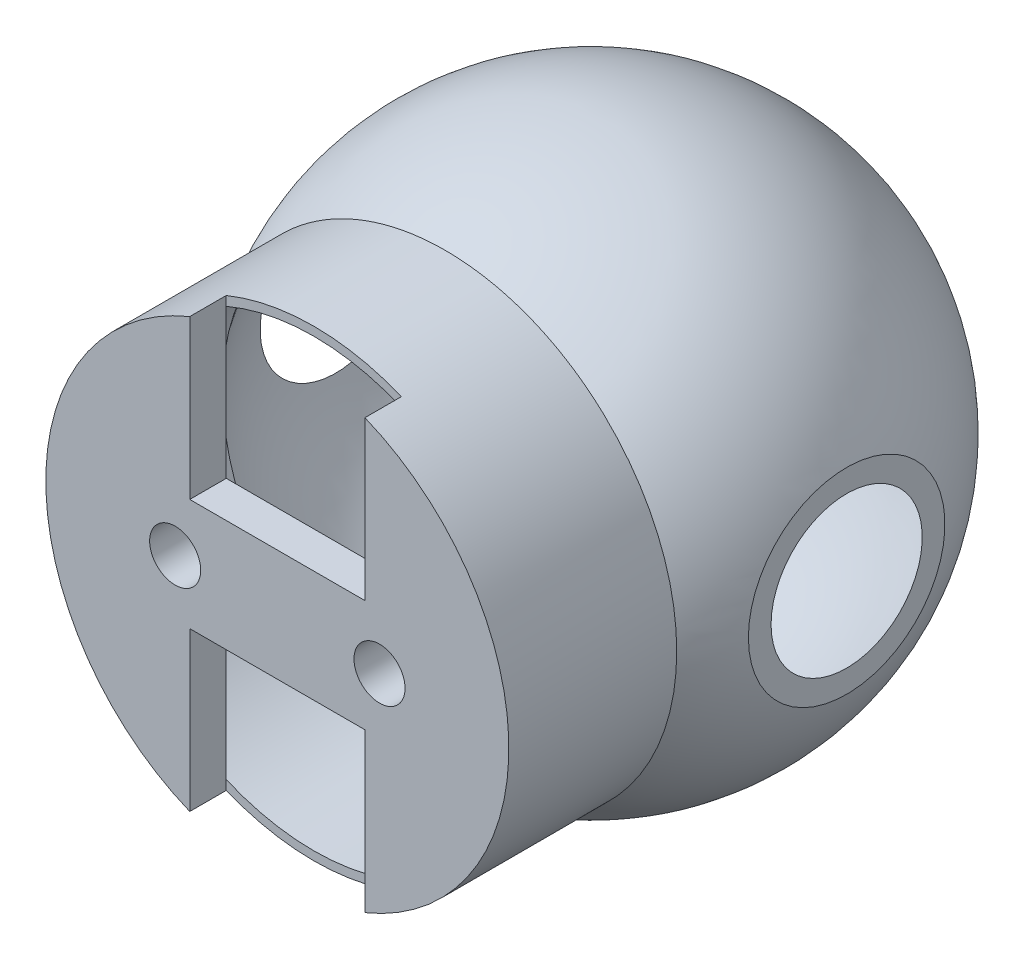
SolidWorks part; units mm, degrees
ref_plane "Front Plane" through (0, 0, 0) normal (0, 0, 1) x (1, 0, 0)
ref_plane "Top Plane" through (0, 0, 0) normal (0, 1, 0) x (1, 0, 0)
ref_plane "Right Plane" through (0, 0, 0) normal (1, 0, 0) x (0, 0, -1)
sketch "Sketch1" plane through (0, 0, 0) normal (0, 0, 1) x (1, 0, 0)
  line L0 (0, 37.5) -> (0, -37.5) construction
  arc A0 (0, -37.5) -> (0, 37.5) centre (0, 0) ccw
  dimension "D1" = 75
revolve "Revolve-Thin4" add sketch "Sketch1" angle 360 about L0 wall 1
ref_plane "Plane1" through (0, 0, 20) normal (0, 0, 1) x (1, 0, 0)
sketch "Sketch2" plane through (0, 0, 20) normal (0, 0, 1) x (1, 0, 0)
  circle A0 centre (0, 0) radius 37.5
  circle A1 centre (0, 0) radius 37.5 construction
extrude "Cut-Extrude1" cut sketch "Sketch2" along normal up to next
ref_plane "Plane3" through (-35, 0, 0) normal (1, 0, 0) x (0, 0, -1)
sketch "Sketch4" plane through (-35, 0, 0) normal (1, 0, 0) x (0, 0, -1)
  circle A0 centre (0, 0) radius 37.5
  arc A1 (-20, -31.7214) -> (-20, 31.7214) centre (0, 0) ccw construction
extrude "Cut-Extrude2" cut sketch "Sketch4" against normal up to next
mirror "Mirror1" about plane through (0, 0, 0) normal (1, 0, 0) of "Cut-Extrude2"
sketch "Sketch5" plane through (0, 0, 20) normal (0, 0, 1) x (1, 0, 0)
  circle A0 centre (0, 0) radius 31.7214
  circle A1 centre (0, 0) radius 31.7214 construction
  circle A2 centre (0, 0) radius 30.5328
  circle A3 centre (0, 0) radius 30.5328 construction
extrude "Boss-Extrude1" add sketch "Sketch5" along normal blind 18
sketch "Sketch6" plane through (0, 0, 38) normal (0, 0, 1) x (1, 0, 0)
  line L0 (-22.5, 0) -> (30.5328, 0) construction
  line L1 (-12, 29.3641) -> (-12, 7.6634)
  line L2 (0, 8.4176) -> (0, -8.4176) construction
  line L3 (-12, 7.6634) -> (12, 7.6634)
  line L4 (-12, -7.6634) -> (-12, -29.3641)
  line L5 (-12, -7.6634) -> (12, -7.6634)
  line L7 (-21.1547, 7.6634) -> (29.8248, -10.8041) construction
  line L8 (-21.1547, -7.6634) -> (21.1547, 7.6634) construction
  line L9 (12, 29.3641) -> (12, 7.6634)
  line L10 (12, -7.6634) -> (12, -29.3641)
  arc A0 (12, -29.3641) -> (12, 29.3641) centre (0, 0) ccw
  arc A1 (-12, 29.3641) -> (-12, -29.3641) centre (0, 0) ccw
  circle A2 centre (0, 0) radius 31.7214 construction
  circle A4 centre (0, 0) radius 30.5328 construction
  circle A12 centre (14, 0) radius 3.5
  circle A13 centre (-14, 0) radius 3.5
  point P0 (0, 0)
  dimension "D1" = 12
  dimension "D2" = 14
  dimension "D3" = 7
extrude "Boss-Extrude2" add sketch "Sketch6" along normal blind 5
